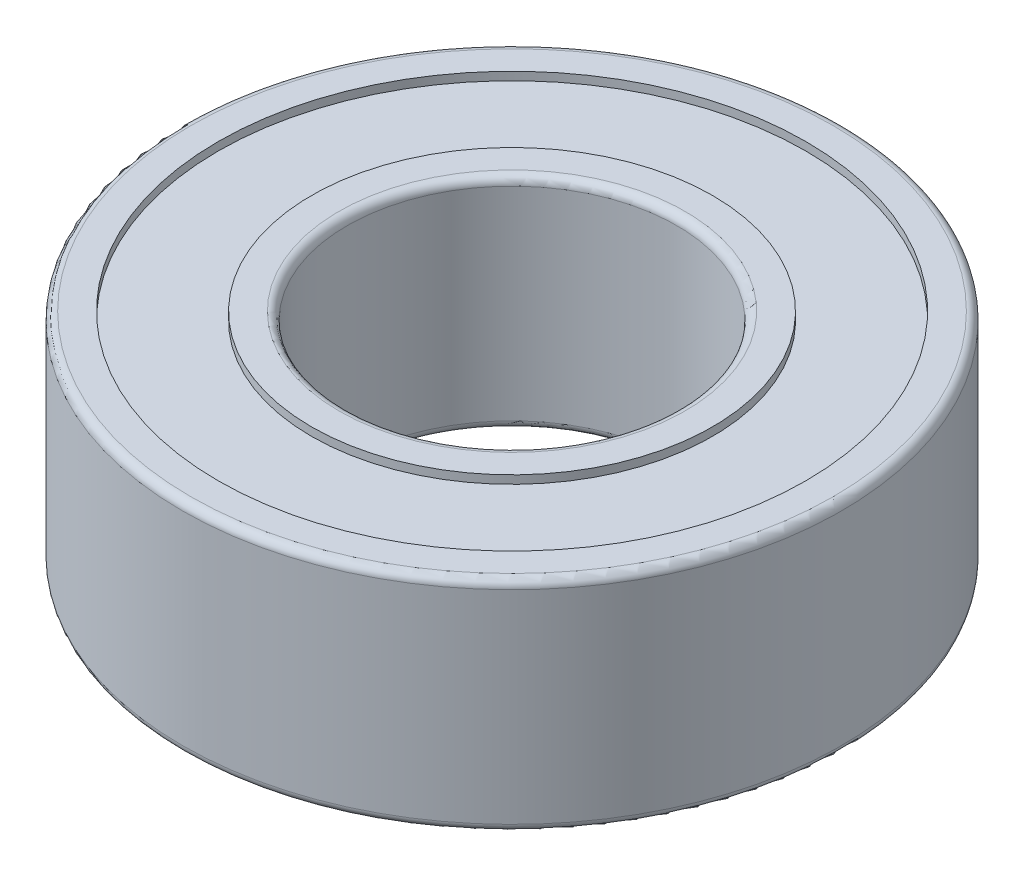
SolidWorks part; units mm, degrees
ref_plane "Plan de face" through (0, 0, 0) normal (0, 0, 1) x (1, 0, 0)
ref_plane "Plan de dessus" through (0, 0, 0) normal (0, 1, 0) x (1, 0, 0)
ref_plane "Plan de droite" through (0, 0, 0) normal (1, 0, 0) x (0, 0, -1)
ref_plane "Plan1" through (0, 0, 0) normal (0, 0, -1) x (-1, 0, 0)
sketch "Esquisse1" plane through (0, 0, 0) normal (0, 0, -1) x (-1, 0, 0)
  line L0 (-3, -1.85) -> (-3, 1.85)
  line L1 (-3.15, 2) -> (-3.65, 2)
  line L2 (-3.65, 2) -> (-3.65, 1.85)
  line L3 (-3.65, 1.85) -> (-5.35, 1.85)
  line L4 (-5.35, 1.85) -> (-5.35, 2)
  line L5 (-5.35, 2) -> (-5.85, 2)
  line L6 (-6, 1.85) -> (-6, -1.85)
  line L7 (-5.85, -2) -> (-5.35, -2)
  line L8 (-5.35, -2) -> (-5.35, -1.85)
  line L9 (-5.35, -1.85) -> (-3.65, -1.85)
  line L10 (-3.65, -1.85) -> (-3.65, -2)
  line L11 (-3.65, -2) -> (-3.15, -2)
  line L12 (0, -2.0034) -> (0, 2.0034) construction
  line L13 (-4.5, 2.3933) -> (-4.5, -2.4549) construction
  arc A0 (-3.15, -2) -> (-3, -1.85) centre (-3.15, -1.85) ccw
  arc A1 (-3, 1.85) -> (-3.15, 2) centre (-3.15, 1.85) ccw
  arc A2 (-5.85, 2) -> (-6, 1.85) centre (-5.85, 1.85) ccw
  arc A3 (-5.85, -2) -> (-6, -1.85) centre (-5.85, -1.85) cw
  point P24 (-4.5, -1.85)
  point P25 (-3, 0)
  dimension "D1" = 0.15
  dimension "D2" = 6
  dimension "D3" = 12
  dimension "D4" = 4
  dimension "D5" = 0.15
  dimension "D6" = 1.7
revolve "Révolution1" add sketch "Esquisse1" angle 360 about L12
